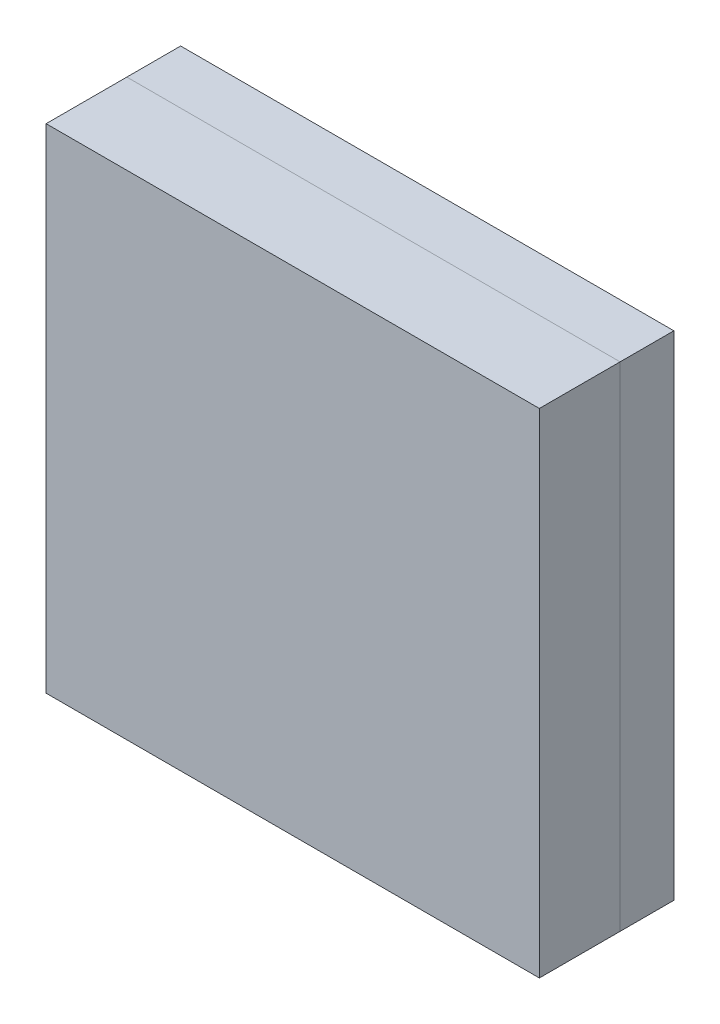
SolidWorks part; units mm, degrees
ref_plane "前视基准面" through (0, 0, 0) normal (0, 0, 1) x (1, 0, 0)
ref_plane "上视基准面" through (0, 0, 0) normal (0, 1, 0) x (1, 0, 0)
ref_plane "右视基准面" through (0, 0, 0) normal (1, 0, 0) x (0, 0, -1)
other "Configuration Table"
sketch "草图2" plane through (0, 0, 0) normal (0, 0, 1) x (1, 0, 0)
  line L1 (0, 0) -> (5.5, 0)
  line L2 (0, 0) -> (0, 5.5)
  line L3 (0, 5.5) -> (5.5, 5.5)
  line L4 (5.5, 0) -> (5.5, 5.5)
  line L5 (0.5, 5) -> (5, 5)
  line L6 (0.5, 5) -> (0.5, 0.5)
  line L7 (0.5, 0.5) -> (5, 0.5)
  line L8 (5, 5) -> (5, 0.5)
  dimension "D1" = 5.5
  dimension "D2" = 5.5
  dimension "D3" = 4.5
  dimension "D4" = 4.5
  dimension "D5" = 0.5
  dimension "D6" = 0.5
extrude "凸台-拉伸2" add sketch "草图2" along normal blind 0.8
sketch "草图3" plane through (0, 0, 0.8) normal (0, 0, 1) x (1, 0, 0)
  line L1 (0, 5.5) -> (5.5, 5.5)
  line L2 (0, 5.5) -> (0, 0)
  line L3 (0, 0) -> (5.5, 0)
  line L4 (5.5, 5.5) -> (5.5, 0)
extrude "凸台-拉伸3" add sketch "草图3" along normal blind 0.2
scale "缩放比例1" [suppressed]
sketch "草图4" plane through (0, 0, 0) normal (0, 0, -1) x (-1, 0, 0)
  line L1 (-5.5, 5.5) -> (0, 5.5)
  line L2 (-5.5, 5.5) -> (-5.5, 0)
  line L3 (-5.5, 0) -> (0, 0)
  line L4 (0, 5.5) -> (0, 0)
extrude "凸台-拉伸4" [suppressed] add sketch "草图4" along normal blind 0.5 separate body
scale "缩放比例2" [suppressed]
scale "缩放比例3" bodies to scale 108 scale about centroid uniform scaling yes scale factor 1
sketch "草图6" plane through (0, 0, 0) normal (0, 0, -1) x (-1, 0, 0)
  line L1 (-5, 5) -> (-0.5, 5)
  line L2 (-5, 5) -> (-5, 0.5)
  line L3 (-5, 0.5) -> (-0.5, 0.5)
  line L4 (-0.5, 5) -> (-0.5, 0.5)
extrude "凸台-拉伸6" [suppressed] add sketch "草图6" against normal blind 0.3
sketch "草图8" plane through (0, 0.5, 0) normal (0, 1, 0) x (1, 0, 0)
  line L3 (0.5, -0.4) -> (5, -0.4)
  line L5 (0.5, -0.8) -> (0.5, 0) construction
  line L6 (5, -0.8) -> (5, 0) construction
sketch "草图5" plane through (0, 0, 0) normal (0, 0, -1) x (-1, 0, 0)
  line L1 (-5.5, 5.5) -> (0, 5.5)
  line L2 (-5.5, 5.5) -> (-5.5, 0)
  line L3 (-5.5, 0) -> (0, 0)
  line L4 (0, 5.5) -> (0, 0)
extrude "凸台-拉伸5" [suppressed] add sketch "草图5" along normal blind 0.5 separate body
sketch "草图10" plane through (0, 0, 1) normal (0, 0, 1) x (1, 0, 0)
  line L1 (0, 5.5) -> (5.5, 5.5)
  line L2 (0, 5.5) -> (0, 0)
  line L3 (0, 0) -> (5.5, 0)
  line L4 (5.5, 5.5) -> (5.5, 0)
extrude "切除-拉伸1" cut sketch "草图10" against normal blind 0.3
extrude "拉伸-薄壁1" [suppressed] add sketch "草图8" along normal up to next thin
sketch "草图11" plane through (0, 0, 0) normal (0, 0, -1) x (-1, 0, 0)
  line L0 (-9.5, 2.75) -> (4, 2.75)
  line L1 (-9.5, -4) -> (-9.5, 9.5) construction
  line L2 (4, 9.5) -> (4, -4) construction
  line L3 (-2.75, 5) -> (-2.75, 0.5)
  line L4 (-5, 5) -> (-0.5, 5) construction
  line L5 (-0.5, 0.5) -> (-5, 0.5) construction
extrude "拉伸-薄壁2" [suppressed] add sketch "草图11" against normal up to next thin contours L3 | L0
sketch "草图12" plane through (0, 0, 0) normal (0, 0, -1) x (-1, 0, 0)
  line L0 (-5, 2.75) -> (-0.5, 2.75)
  line L1 (-5, 0.5) -> (-5, 5) construction
  line L2 (-0.5, 5) -> (-0.5, 0.5) construction
  line L3 (-2.75, 5) -> (-2.75, 0.5)
  line L4 (-5, 5) -> (-0.5, 5) construction
  line L5 (-0.5, 0.5) -> (-5, 0.5) construction
sketch "草图13" plane through (0, 0, 0.7) normal (0, 0, 1) x (1, 0, 0)
  line L1 (0, 5.5) -> (5.5, 5.5)
  line L2 (0, 5.5) -> (0, 0)
  line L3 (0, 0) -> (5.5, 0)
  line L4 (5.5, 5.5) -> (5.5, 0)
extrude "凸台-拉伸7" add sketch "草图13" along normal blind 0.2
extrude "拉伸-薄壁3" add sketch "草图12" against normal up to surface (0.7 mm away) thin up to face at (2.75, 2.75, 0.7) thin type mid plane wall 1.5
sketch "草图14" plane through (0, 0, 0) normal (0, 0, -1) x (-1, 0, 0)
  line L1 (-5.5, 5.5) -> (0, 5.5)
  line L2 (-5.5, 5.5) -> (-5.5, 0)
  line L3 (-5.5, 0) -> (0, 0)
  line L4 (0, 5.5) -> (0, 0)
extrude "凸台-拉伸8" add sketch "草图14" along normal blind 0.6 separate body
sketch "草图15" plane through (5, 0, 0) normal (-1, 0, 0) x (0, 0, 1)
  line L0 (0.35, 5) -> (0.35, 0.5)
  line L1 (0.7, 5) -> (0, 5) construction
  line L2 (0.7, 0.5) -> (0, 0.5) construction
extrude "拉伸-薄壁4" add sketch "草图15" along normal through all thin
